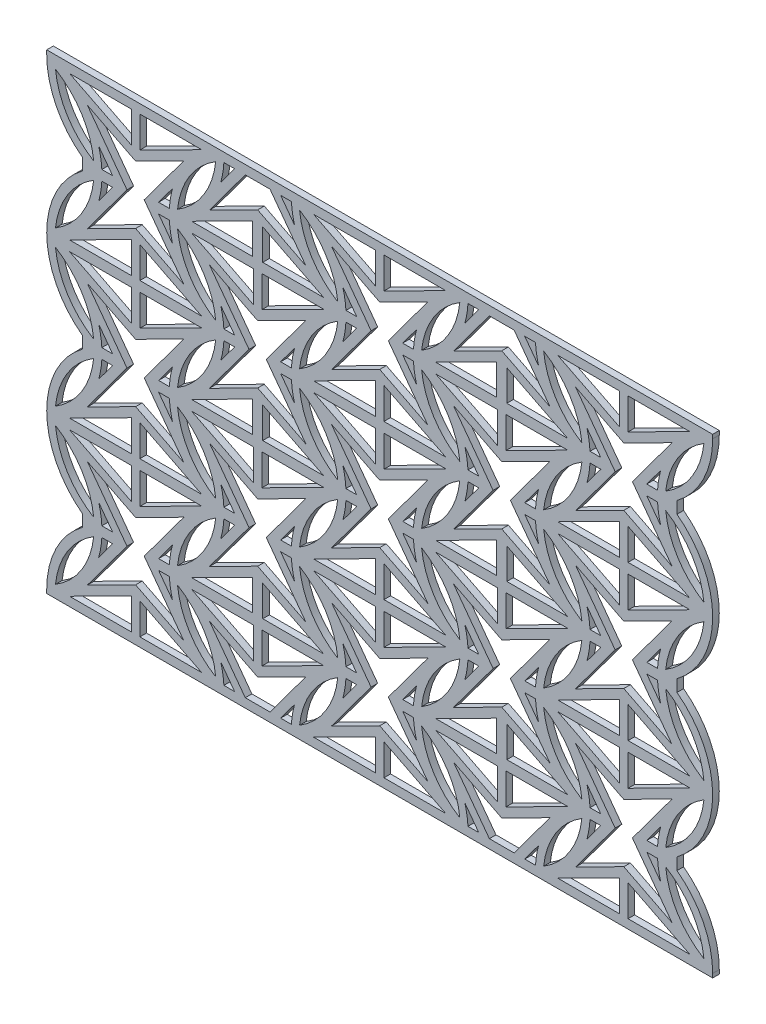
SolidWorks part; units mm, degrees
ref_plane "Front Plane" through (0, 0, 0) normal (0, 0, 1) x (1, 0, 0)
ref_plane "Top Plane" through (0, 0, 0) normal (0, 1, 0) x (1, 0, 0)
ref_plane "Right Plane" through (0, 0, 0) normal (1, 0, 0) x (0, 0, -1)
sketch "Sketch1" plane through (0, 0, 0) normal (0, 0, 1) x (1, 0, 0)
  line L1 (4.5382, 0.1047) -> (6.4871, 0.1047)
  line L3 (-15.7279, 14.9993) -> (-15.7279, 15.7158) construction
  line L6 (16.4721, 15.7158) -> (16.4721, 14.9993) construction
  line L8 (-3.7941, 0.1047) -> (-5.743, 0.1047)
  line L9 (-15.7279, -12.9529) -> (-15.7279, -13.6694)
  line L10 (-3.7941, 1.9417) -> (-6.3088, 5.3386)
  line L11 (-15.7279, -13.6694) -> (16.4721, -13.6694)
  line L13 (-9.2665, 2.1033) -> (-9.2665, -0.0569)
  line L16 (-15.7279, 14.9993) -> (16.4721, 14.9993) construction
  line L17 (12.3361, 14.0808) -> (1.1455, 14.0808)
  line L21 (4.5382, 1.9417) -> (7.053, 5.3386)
  line L23 (-0.4014, 8.4288) -> (-11.592, 14.0808)
  line L24 (4.5382, 0.1047) -> (7.053, -3.2922)
  line L25 (4.5382, 1.9417) -> (6.4871, 1.9417)
  line L27 (-3.7941, 0.1047) -> (-6.3088, -3.2922)
  line L28 (-3.7941, 1.9417) -> (-5.743, 1.9417)
  line L30 (-15.7279, 15.7158) -> (16.4721, 15.7158) construction
  line L31 (-0.4014, 14.0808) -> (-11.592, 14.0808)
  line L33 (16.4721, -13.6694) -> (16.4721, -12.9529) construction
  line L34 (-15.7279, -12.9529) -> (16.4721, -12.9529) construction
  line L36 (10.0106, 2.1033) -> (10.0106, -0.0569) construction
  line L40 (1.1455, 8.4288) -> (12.3361, 14.0808)
  line L41 (0.3721, 6.3052) -> (9.1118, 10.7193)
  line L42 (9.1118, 10.7193) -> (1.9335, 1.0232)
  line L43 (9.1118, -8.6729) -> (1.9335, 1.0232)
  line L44 (0.3721, -4.2588) -> (9.1118, -8.6729)
  line L45 (0.3721, -4.2588) -> (-8.3677, -8.6729)
  line L46 (-8.3677, -8.6729) -> (-1.1894, 1.0232)
  line L47 (-8.3677, 10.7193) -> (-1.1894, 1.0232)
  line L48 (0.3721, 6.3052) -> (-8.3677, 10.7193)
  line L49 (-1.1894, 1.0232) -> (49998.8106, 1.0232) construction
  line L50 (0.3721, 6.3052) -> (0.3721, -49993.6948) construction
  line L51 (-0.4014, 14.0808) -> (-0.4014, 8.4288)
  line L52 (1.1455, 14.0808) -> (1.1455, 8.4288)
  line L53 (21.7061, 22.405) -> (10.5155, 28.0569)
  line L54 (22.4795, 20.2814) -> (13.7398, 24.6955)
  line L55 (26.6457, 15.9179) -> (29.1604, 19.3147)
  line L56 (6.3795, 1.0232) -> (6.3795, 0.3067) construction
  line L57 (21.7061, 28.0569) -> (10.5155, 28.0569)
  line L58 (32.118, 16.0794) -> (32.118, 13.9193) construction
  line L59 (18.3134, 15.9179) -> (15.7986, 19.3147)
  line L60 (18.3134, 15.9179) -> (16.3645, 15.9179)
  line L61 (23.403, 7.5179) -> (34.4436, 1.9417)
  line L62 (26.6457, 15.9179) -> (28.5946, 15.9179)
  line L63 (6.3795, 28.9755) -> (38.5795, 28.9755) construction
  line L64 (18.3134, 14.0808) -> (16.3645, 14.0808)
  line L65 (34.4436, 1.9417) -> (23.403, 1.9417)
  line L66 (21.5561, 2.1033) -> (21.5561, 1.9417)
  line L67 (38.5795, 0.3067) -> (38.5795, 1.0232) construction
  line L68 (26.6457, 14.0808) -> (28.5946, 14.0808)
  line L69 (13.7398, 5.3032) -> (20.918, 14.9993)
  line L70 (23.253, 28.0569) -> (23.253, 22.405)
  line L71 (21.5561, 1.9417) -> (10.5155, 1.9417)
  line L72 (22.4795, 9.7173) -> (31.2192, 5.3032)
  line L73 (6.3795, 1.0232) -> (38.5795, 1.0232) construction
  line L74 (23.403, 7.5179) -> (23.403, 1.9417)
  line L75 (22.4795, 9.7173) -> (13.7398, 5.3032)
  line L76 (6.3795, 28.9755) -> (6.3795, 29.6919) construction
  line L77 (18.3134, 14.0808) -> (15.7986, 10.6839)
  line L78 (12.841, 16.0794) -> (12.841, 13.9193) construction
  line L79 (31.2192, 24.6955) -> (24.041, 14.9993)
  line L80 (21.5561, 7.5179) -> (21.5561, 2.1033)
  line L81 (22.4795, 20.2814) -> (31.2192, 24.6955)
  line L82 (6.3795, 0.3067) -> (38.5795, 0.3067) construction
  line L83 (21.7061, 28.0569) -> (21.7061, 22.405)
  line L84 (21.5561, 7.5179) -> (10.5155, 1.9417)
  line L85 (23.253, 22.405) -> (34.4436, 28.0569)
  line L86 (6.3795, 29.6919) -> (38.5795, 29.6919) construction
  line L87 (26.6457, 14.0808) -> (29.1604, 10.6839)
  line L88 (31.2192, 5.3032) -> (24.041, 14.9993)
  line L89 (38.5795, 29.6919) -> (38.5795, 28.9755) construction
  line L90 (34.4436, 28.0569) -> (23.253, 28.0569)
  line L91 (13.7398, 24.6955) -> (20.918, 14.9993)
  line L92 (43.8135, 36.3811) -> (32.6229, 42.0331)
  line L93 (44.587, 34.2575) -> (35.8472, 38.6716)
  line L94 (48.7531, 29.894) -> (51.2679, 33.2909)
  line L95 (28.487, 14.9993) -> (28.487, 14.2829) construction
  line L96 (43.8135, 42.0331) -> (32.6229, 42.0331)
  line L97 (54.2255, 30.0555) -> (54.2255, 27.8954) construction
  line L98 (40.4208, 29.894) -> (37.9061, 33.2909)
  line L99 (40.4208, 29.894) -> (38.4719, 29.894)
  line L101 (48.7531, 29.894) -> (50.702, 29.894)
  line L102 (28.487, 42.9516) -> (60.687, 42.9516) construction
  line L103 (40.4208, 28.0569) -> (38.4719, 28.0569)
  line L106 (60.687, 14.2829) -> (60.687, 14.9993) construction
  line L107 (48.7531, 28.0569) -> (50.702, 28.0569)
  line L108 (35.8472, 19.2793) -> (43.0255, 28.9755)
  line L109 (45.3604, 42.0331) -> (45.3604, 36.3811)
  line L111 (44.587, 23.6935) -> (53.3267, 19.2793)
  line L112 (28.487, 14.9993) -> (60.687, 14.9993) construction
  line L114 (44.587, 23.6935) -> (35.8472, 19.2793)
  line L115 (28.487, 42.9516) -> (28.487, 43.6681) construction
  line L116 (40.4208, 28.0569) -> (37.9061, 24.6601)
  line L117 (34.9484, 30.0555) -> (34.9484, 27.8954) construction
  line L118 (53.3267, 38.6716) -> (46.1484, 28.9755)
  line L120 (44.587, 34.2575) -> (53.3267, 38.6716)
  line L121 (28.487, 14.2829) -> (60.687, 14.2829) construction
  line L122 (43.8135, 42.0331) -> (43.8135, 36.3811)
  line L124 (45.3604, 36.3811) -> (56.551, 42.0331)
  line L125 (28.487, 43.6681) -> (60.687, 43.6681) construction
  line L126 (48.7531, 28.0569) -> (51.2679, 24.6601)
  line L127 (53.3267, 19.2793) -> (46.1484, 28.9755)
  line L128 (60.687, 43.6681) -> (60.687, 42.9516) construction
  line L129 (56.551, 42.0331) -> (45.3604, 42.0331)
  line L130 (35.8472, 38.6716) -> (43.0255, 28.9755)
  line L131 (66.6944, 37.6696) -> (75.4341, 33.2555)
  line L132 (65.921, 56.0092) -> (65.921, 50.3572)
  line L133 (82.7944, 57.6442) -> (82.7944, 56.9278) construction
  line L134 (70.8605, 43.8701) -> (73.3753, 47.267)
  line L135 (65.921, 50.3572) -> (54.7304, 56.0092)
  line L136 (66.6944, 48.2336) -> (75.4341, 52.6478)
  line L137 (50.5944, 28.9755) -> (50.5944, 28.259) construction
  line L138 (65.771, 35.4702) -> (54.7304, 29.894)
  line L139 (62.5283, 42.0331) -> (60.0135, 38.6362)
  line L140 (66.6944, 37.6696) -> (57.9547, 33.2555)
  line L141 (50.5944, 56.9278) -> (82.7944, 56.9278) construction
  line L142 (78.6585, 56.0092) -> (67.4679, 56.0092)
  line L143 (65.921, 56.0092) -> (54.7304, 56.0092)
  line L144 (57.9547, 33.2555) -> (65.1329, 42.9516)
  line L145 (50.5944, 28.259) -> (82.7944, 28.259) construction
  line L146 (75.4341, 33.2555) -> (68.2559, 42.9516)
  line L147 (62.5283, 43.8701) -> (60.0135, 47.267)
  line L148 (66.6944, 48.2336) -> (57.9547, 52.6478)
  line L149 (76.3329, 44.0317) -> (76.3329, 41.8716) construction
  line L150 (65.771, 35.4702) -> (65.771, 30.0555)
  line L151 (67.4679, 50.3572) -> (78.6585, 56.0092)
  line L152 (57.0559, 44.0317) -> (57.0559, 41.8716) construction
  line L153 (50.5944, 57.6442) -> (82.7944, 57.6442) construction
  line L154 (65.771, 29.894) -> (54.7304, 29.894)
  line L155 (78.6585, 29.894) -> (67.6179, 29.894)
  line L156 (82.7944, 28.259) -> (82.7944, 28.9755) construction
  line L157 (62.5283, 42.0331) -> (60.5794, 42.0331)
  line L158 (70.8605, 43.8701) -> (72.8095, 43.8701)
  line L159 (65.771, 30.0555) -> (65.771, 29.894)
  line L160 (67.6179, 35.4702) -> (78.6585, 29.894)
  line L161 (62.5283, 43.8701) -> (60.5794, 43.8701)
  line L162 (67.6179, 35.4702) -> (67.6179, 29.894)
  line L163 (50.5944, 28.9755) -> (82.7944, 28.9755) construction
  line L164 (70.8605, 42.0331) -> (72.8095, 42.0331)
  line L165 (70.8605, 42.0331) -> (73.3753, 38.6362)
  line L166 (75.4341, 52.6478) -> (68.2559, 42.9516)
  line L167 (57.9547, 52.6478) -> (65.1329, 42.9516)
  line L168 (50.5944, 56.9278) -> (50.5944, 57.6442) construction
  line L169 (67.4679, 56.0092) -> (67.4679, 50.3572)
  line L170 (26.6457, 43.8701) -> (29.1604, 47.267)
  line L171 (26.6457, 42.0331) -> (29.1604, 38.6362)
  line L172 (21.5561, 30.0555) -> (21.5561, 29.894)
  line L173 (23.403, 35.4702) -> (23.403, 29.894)
  line L174 (38.5795, 28.259) -> (38.5795, 28.9755) construction
  line L175 (23.403, 35.4702) -> (34.4436, 29.894)
  line L176 (23.253, 50.3572) -> (34.4436, 56.0092)
  line L177 (6.3795, 28.9755) -> (6.3795, 28.259) construction
  line L178 (34.4436, 56.0092) -> (23.253, 56.0092)
  line L179 (34.4436, 29.894) -> (23.403, 29.894)
  line L180 (22.4795, 37.6696) -> (31.2192, 33.2555)
  line L181 (6.3795, 56.9278) -> (6.3795, 57.6442) construction
  line L182 (21.7061, 50.3572) -> (10.5155, 56.0092)
  line L183 (22.4795, 37.6696) -> (13.7398, 33.2555)
  line L184 (21.5561, 35.4702) -> (21.5561, 30.0555)
  line L185 (6.3795, 56.9278) -> (38.5795, 56.9278) construction
  line L186 (21.5561, 35.4702) -> (10.5155, 29.894)
  line L187 (22.4795, 48.2336) -> (13.7398, 52.6478)
  line L188 (23.253, 56.0092) -> (23.253, 50.3572)
  line L189 (21.5561, 29.894) -> (10.5155, 29.894)
  line L190 (12.841, 44.0317) -> (12.841, 41.8716) construction
  line L191 (32.118, 44.0317) -> (32.118, 41.8716) construction
  line L192 (26.6457, 42.0331) -> (28.5946, 42.0331)
  line L193 (21.7061, 56.0092) -> (10.5155, 56.0092)
  line L194 (18.3134, 42.0331) -> (16.3645, 42.0331)
  line L195 (13.7398, 52.6478) -> (20.918, 42.9516)
  line L196 (18.3134, 43.8701) -> (16.3645, 43.8701)
  line L197 (31.2192, 33.2555) -> (24.041, 42.9516)
  line L198 (6.3795, 28.259) -> (38.5795, 28.259) construction
  line L199 (18.3134, 42.0331) -> (15.7986, 38.6362)
  line L200 (13.7398, 33.2555) -> (20.918, 42.9516)
  line L201 (22.4795, 48.2336) -> (31.2192, 52.6478)
  line L202 (38.5795, 57.6442) -> (38.5795, 56.9278) construction
  line L203 (18.3134, 43.8701) -> (15.7986, 47.267)
  line L204 (31.2192, 52.6478) -> (24.041, 42.9516)
  line L205 (6.3795, 28.9755) -> (38.5795, 28.9755) construction
  line L206 (21.7061, 56.0092) -> (21.7061, 50.3572)
  line L207 (26.6457, 43.8701) -> (28.5946, 43.8701)
  line L208 (6.3795, 57.6442) -> (38.5795, 57.6442) construction
  line L209 (4.5382, 29.894) -> (7.053, 33.2909)
  line L210 (4.5382, 28.0569) -> (7.053, 24.6601)
  line L213 (16.4721, 14.2829) -> (16.4721, 14.9993) construction
  line L215 (1.1455, 36.3811) -> (12.3361, 42.0331)
  line L216 (-15.7279, 14.9993) -> (-15.7279, 14.2829) construction
  line L217 (12.3361, 42.0331) -> (1.1455, 42.0331)
  line L219 (0.3721, 23.6935) -> (9.1118, 19.2793)
  line L220 (-15.7279, 42.9516) -> (-15.7279, 43.6681) construction
  line L221 (-0.4014, 36.3811) -> (-11.592, 42.0331)
  line L222 (0.3721, 23.6935) -> (-8.3677, 19.2793)
  line L224 (-15.7279, 42.9516) -> (16.4721, 42.9516) construction
  line L226 (0.3721, 34.2575) -> (-8.3677, 38.6716)
  line L227 (1.1455, 42.0331) -> (1.1455, 36.3811)
  line L229 (-9.2665, 30.0555) -> (-9.2665, 27.8954)
  line L230 (10.0106, 30.0555) -> (10.0106, 27.8954) construction
  line L231 (4.5382, 28.0569) -> (6.4871, 28.0569)
  line L232 (-0.4014, 42.0331) -> (-11.592, 42.0331)
  line L233 (-3.7941, 28.0569) -> (-5.743, 28.0569)
  line L234 (-8.3677, 38.6716) -> (-1.1894, 28.9755)
  line L235 (-3.7941, 29.894) -> (-5.743, 29.894)
  line L236 (9.1118, 19.2793) -> (1.9335, 28.9755)
  line L237 (-15.7279, 14.2829) -> (16.4721, 14.2829) construction
  line L238 (-3.7941, 28.0569) -> (-6.3088, 24.6601)
  line L239 (-8.3677, 19.2793) -> (-1.1894, 28.9755)
  line L240 (0.3721, 34.2575) -> (9.1118, 38.6716)
  line L241 (16.4721, 43.6681) -> (16.4721, 42.9516) construction
  line L242 (-3.7941, 29.894) -> (-6.3088, 33.2909)
  line L243 (9.1118, 38.6716) -> (1.9335, 28.9755)
  line L244 (-15.7279, 14.9993) -> (16.4721, 14.9993) construction
  line L245 (-0.4014, 42.0331) -> (-0.4014, 36.3811)
  line L246 (4.5382, 29.894) -> (6.4871, 29.894)
  line L247 (-15.7279, 43.6681) -> (16.4721, 43.6681) construction
  line L248 (48.7531, 57.8463) -> (51.2679, 61.2432)
  line L249 (48.7531, 56.0092) -> (51.2679, 52.6123)
  line L252 (60.687, 42.2352) -> (60.687, 42.9516) construction
  line L254 (45.3604, 64.3334) -> (56.551, 69.9854)
  line L255 (28.487, 42.9516) -> (28.487, 42.2352) construction
  line L256 (56.551, 69.9854) -> (45.3604, 69.9854)
  line L258 (44.587, 51.6457) -> (53.3267, 47.2316)
  line L259 (28.487, 70.9039) -> (28.487, 71.6203) construction
  line L260 (43.8135, 64.3334) -> (32.6229, 69.9854)
  line L261 (44.587, 51.6457) -> (35.8472, 47.2316)
  line L263 (28.487, 70.9039) -> (60.687, 70.9039) construction
  line L265 (44.587, 62.2098) -> (35.8472, 66.6239)
  line L266 (45.3604, 69.9854) -> (45.3604, 64.3334)
  line L268 (34.9484, 58.0078) -> (34.9484, 55.8477) construction
  line L269 (54.2255, 58.0078) -> (54.2255, 55.8477) construction
  line L270 (48.7531, 56.0092) -> (50.702, 56.0092)
  line L271 (43.8135, 69.9854) -> (32.6229, 69.9854)
  line L272 (40.4208, 56.0092) -> (38.4719, 56.0092)
  line L273 (35.8472, 66.6239) -> (43.0255, 56.9278)
  line L274 (40.4208, 57.8463) -> (38.4719, 57.8463)
  line L275 (53.3267, 47.2316) -> (46.1484, 56.9278)
  line L276 (28.487, 42.2352) -> (60.687, 42.2352) construction
  line L277 (40.4208, 56.0092) -> (37.9061, 52.6123)
  line L278 (35.8472, 47.2316) -> (43.0255, 56.9278)
  line L279 (44.587, 62.2098) -> (53.3267, 66.6239)
  line L280 (60.687, 71.6203) -> (60.687, 70.9039) construction
  line L281 (40.4208, 57.8463) -> (37.9061, 61.2432)
  line L282 (53.3267, 66.6239) -> (46.1484, 56.9278)
  line L283 (28.487, 42.9516) -> (60.687, 42.9516) construction
  line L284 (43.8135, 69.9854) -> (43.8135, 64.3334)
  line L285 (48.7531, 57.8463) -> (50.702, 57.8463)
  line L286 (28.487, 71.6203) -> (60.687, 71.6203)
  line L287 (4.5382, 57.8463) -> (7.053, 61.2432)
  line L288 (4.5382, 56.0092) -> (7.053, 52.6123)
  line L291 (16.4721, 42.2352) -> (16.4721, 42.9516) construction
  line L293 (1.1455, 64.3334) -> (12.3361, 69.9854)
  line L294 (-15.7279, 42.9516) -> (-15.7279, 42.2352) construction
  line L295 (12.3361, 69.9854) -> (1.1455, 69.9854)
  line L297 (0.3721, 51.6457) -> (9.1118, 47.2316)
  line L298 (-15.7279, 70.9039) -> (-15.7279, 71.6203)
  line L299 (-0.4014, 64.3334) -> (-11.592, 69.9854)
  line L300 (0.3721, 51.6457) -> (-8.3677, 47.2316)
  line L302 (-15.7279, 70.9039) -> (16.4721, 70.9039) construction
  line L304 (0.3721, 62.2098) -> (-8.3677, 66.6239)
  line L305 (1.1455, 69.9854) -> (1.1455, 64.3334)
  line L307 (-9.2665, 58.0078) -> (-9.2665, 55.8477)
  line L308 (10.0106, 58.0078) -> (10.0106, 55.8477) construction
  line L309 (4.5382, 56.0092) -> (6.4871, 56.0092)
  line L310 (-0.4014, 69.9854) -> (-11.592, 69.9854)
  line L311 (-3.7941, 56.0092) -> (-5.743, 56.0092)
  line L312 (-8.3677, 66.6239) -> (-1.1894, 56.9278)
  line L313 (-3.7941, 57.8463) -> (-5.743, 57.8463)
  line L314 (9.1118, 47.2316) -> (1.9335, 56.9278)
  line L315 (-15.7279, 42.2352) -> (16.4721, 42.2352) construction
  line L316 (-3.7941, 56.0092) -> (-6.3088, 52.6123)
  line L317 (-8.3677, 47.2316) -> (-1.1894, 56.9278)
  line L318 (0.3721, 62.2098) -> (9.1118, 66.6239)
  line L319 (16.4721, 71.6203) -> (16.4721, 70.9039) construction
  line L320 (-3.7941, 57.8463) -> (-6.3088, 61.2432)
  line L321 (9.1118, 66.6239) -> (1.9335, 56.9278)
  line L322 (-15.7279, 42.9516) -> (16.4721, 42.9516) construction
  line L323 (-0.4014, 69.9854) -> (-0.4014, 64.3334)
  line L324 (4.5382, 57.8463) -> (6.4871, 57.8463)
  line L325 (-15.7279, 71.6203) -> (16.4721, 71.6203)
  line L326 (26.6457, 71.8224) -> (29.1604, 75.2193) construction
  line L327 (26.6457, 69.9854) -> (29.1604, 66.5885)
  line L328 (21.5561, 58.0078) -> (21.5561, 57.8463)
  line L329 (23.403, 63.4225) -> (23.403, 57.8463)
  line L330 (38.5795, 56.2113) -> (38.5795, 56.9278) construction
  line L331 (23.403, 63.4225) -> (34.4436, 57.8463)
  line L332 (23.253, 78.3095) -> (34.4436, 83.9615) construction
  line L333 (6.3795, 56.9278) -> (6.3795, 56.2113) construction
  line L334 (34.4436, 83.9615) -> (23.253, 83.9615) construction
  line L335 (34.4436, 57.8463) -> (23.403, 57.8463)
  line L336 (22.4795, 65.6219) -> (31.2192, 61.2078)
  line L337 (6.3795, 84.88) -> (6.3795, 85.5965) construction
  line L338 (21.7061, 78.3095) -> (10.5155, 83.9615) construction
  line L339 (22.4795, 65.6219) -> (13.7398, 61.2078)
  line L340 (21.5561, 63.4225) -> (21.5561, 58.0078)
  line L341 (6.3795, 84.88) -> (38.5795, 84.88) construction
  line L342 (21.5561, 63.4225) -> (10.5155, 57.8463)
  line L344 (23.253, 83.9615) -> (23.253, 78.3095) construction
  line L345 (21.5561, 57.8463) -> (10.5155, 57.8463)
  line L346 (12.841, 71.9839) -> (12.841, 69.8665) construction
  line L347 (32.118, 71.9839) -> (32.118, 69.7811) construction
  line L348 (26.6457, 69.9854) -> (28.5946, 69.9854)
  line L349 (21.7061, 83.9615) -> (10.5155, 83.9615) construction
  line L350 (18.3134, 69.9854) -> (16.3645, 69.9854)
  line L352 (18.3134, 71.8224) -> (16.3645, 71.8224) construction
  line L353 (31.2192, 61.2078) -> (24.721, 69.9854)
  line L354 (6.3795, 56.2113) -> (38.5795, 56.2113) construction
  line L355 (18.3134, 69.9854) -> (15.7986, 66.5885)
  line L356 (13.7398, 61.2078) -> (20.238, 69.9854)
  line L358 (38.5795, 85.5965) -> (38.5795, 84.88) construction
  line L359 (18.3134, 71.8224) -> (15.7986, 75.2193) construction
  line L361 (6.3795, 56.9278) -> (38.5795, 56.9278) construction
  line L362 (21.7061, 83.9615) -> (21.7061, 78.3095) construction
  line L363 (26.6457, 71.8224) -> (28.5946, 71.8224) construction
  line L364 (6.3795, 85.5965) -> (38.5795, 85.5965) construction
  line L365 (53.3267, 10.7193) -> (46.1484, 1.0232)
  line L366 (44.587, 6.3052) -> (35.8472, 10.7193)
  line L367 (28.487, -13.6694) -> (60.687, -13.6694)
  line L368 (40.4208, 0.1047) -> (37.9061, -3.2922)
  line L369 (54.2255, 2.1033) -> (54.2255, -0.0569) construction
  line L370 (43.8135, 8.4288) -> (32.6229, 14.0808)
  line L371 (28.487, -12.9529) -> (28.487, -13.6694) construction
  line L373 (28.487, 15.7158) -> (60.687, 15.7158) construction
  line L374 (48.7531, 0.1047) -> (51.2679, -3.2922)
  line L375 (28.487, 14.9993) -> (28.487, 15.7158) construction
  line L376 (48.7531, 0.1047) -> (50.702, 0.1047)
  line L377 (45.3604, 8.4288) -> (56.551, 14.0808)
  line L378 (35.8472, 10.7193) -> (43.0255, 1.0232)
  line L379 (40.4208, 1.9417) -> (37.9061, 5.3386)
  line L381 (44.587, -4.2588) -> (35.8472, -8.6729)
  line L382 (40.4208, 0.1047) -> (38.4719, 0.1047)
  line L383 (48.7531, 1.9417) -> (50.702, 1.9417)
  line L384 (34.9484, 2.1033) -> (34.9484, -0.0569) construction
  line L385 (56.551, 14.0808) -> (45.3604, 14.0808)
  line L386 (48.7531, 1.9417) -> (51.2679, 5.3386)
  line L387 (43.8135, 14.0808) -> (32.6229, 14.0808)
  line L388 (28.487, -12.9529) -> (60.687, -12.9529) construction
  line L390 (35.8472, -8.6729) -> (43.0255, 1.0232)
  line L391 (28.487, 14.9993) -> (60.687, 14.9993) construction
  line L393 (53.3267, -8.6729) -> (46.1484, 1.0232)
  line L394 (60.687, -13.6694) -> (60.687, -12.9529) construction
  line L395 (40.4208, 1.9417) -> (38.4719, 1.9417)
  line L396 (43.8135, 14.0808) -> (43.8135, 8.4288)
  line L398 (44.587, 6.3052) -> (53.3267, 10.7193)
  line L400 (44.587, -4.2588) -> (53.3267, -8.6729)
  line L402 (45.3604, 14.0808) -> (45.3604, 8.4288)
  line L403 (60.687, 15.7158) -> (60.687, 14.9993) construction
  line L404 (75.4341, 24.6955) -> (68.2559, 14.9993)
  line L405 (66.6944, 20.2814) -> (57.9547, 24.6955)
  line L406 (50.5944, 0.3067) -> (82.7944, 0.3067) construction
  line L407 (62.5283, 14.0808) -> (60.0135, 10.6839)
  line L408 (76.3329, 16.0794) -> (76.3329, 13.9193) construction
  line L409 (65.921, 22.405) -> (54.7304, 28.0569)
  line L410 (50.5944, 1.0232) -> (50.5944, 0.3067) construction
  line L411 (67.6179, 7.5179) -> (78.6585, 1.9417)
  line L412 (50.5944, 29.6919) -> (82.7944, 29.6919) construction
  line L413 (70.8605, 14.0808) -> (73.3753, 10.6839)
  line L414 (50.5944, 28.9755) -> (50.5944, 29.6919) construction
  line L415 (70.8605, 14.0808) -> (72.8095, 14.0808)
  line L416 (67.4679, 22.405) -> (78.6585, 28.0569)
  line L417 (57.9547, 24.6955) -> (65.1329, 14.9993)
  line L418 (62.5283, 15.9179) -> (60.0135, 19.3147)
  line L419 (78.6585, 1.9417) -> (67.6179, 1.9417)
  line L420 (66.6944, 9.7173) -> (57.9547, 5.3032)
  line L421 (62.5283, 14.0808) -> (60.5794, 14.0808)
  line L422 (70.8605, 15.9179) -> (72.8095, 15.9179)
  line L423 (57.0559, 16.0794) -> (57.0559, 13.9193) construction
  line L424 (78.6585, 28.0569) -> (67.4679, 28.0569)
  line L425 (70.8605, 15.9179) -> (73.3753, 19.3147)
  line L426 (65.921, 28.0569) -> (54.7304, 28.0569)
  line L427 (50.5944, 1.0232) -> (82.7944, 1.0232) construction
  line L428 (67.6179, 7.5179) -> (67.6179, 1.9417)
  line L429 (57.9547, 5.3032) -> (65.1329, 14.9993)
  line L430 (50.5944, 28.9755) -> (82.7944, 28.9755) construction
  line L431 (65.771, 1.9417) -> (54.7304, 1.9417)
  line L432 (75.4341, 5.3032) -> (68.2559, 14.9993)
  line L433 (82.7944, 0.3067) -> (82.7944, 1.0232) construction
  line L434 (62.5283, 15.9179) -> (60.5794, 15.9179)
  line L435 (65.921, 28.0569) -> (65.921, 22.405)
  line L436 (65.771, 7.5179) -> (65.771, 2.1033)
  line L437 (66.6944, 20.2814) -> (75.4341, 24.6955)
  line L438 (65.771, 7.5179) -> (54.7304, 1.9417)
  line L439 (66.6944, 9.7173) -> (75.4341, 5.3032)
  line L440 (65.771, 2.1033) -> (65.771, 1.9417)
  line L441 (67.4679, 28.0569) -> (67.4679, 22.405)
  line L442 (82.7944, 29.6919) -> (82.7944, 28.9755) construction
  line L443 (65.921, 83.9615) -> (54.7304, 83.9615) construction
  line L444 (67.4679, 78.3095) -> (78.6585, 83.9615) construction
  line L446 (78.6585, 83.9615) -> (67.4679, 83.9615) construction
  line L448 (82.7944, 85.5965) -> (82.7944, 84.88) construction
  line L449 (66.6944, 65.6219) -> (57.9547, 61.2078)
  line L450 (50.5944, 84.88) -> (50.5944, 85.5965) construction
  line L451 (57.0559, 71.9839) -> (57.0559, 69.8238) construction
  line L452 (70.8605, 69.9854) -> (73.3753, 66.5885)
  line L454 (82.7944, 56.2113) -> (82.7944, 56.9278) construction
  line L455 (62.5283, 71.8224) -> (60.0135, 75.2193) construction
  line L456 (62.5283, 69.9854) -> (60.0135, 66.5885)
  line L457 (65.921, 83.9615) -> (65.921, 78.3095) construction
  line L458 (76.3329, 71.9839) -> (76.3329, 69.8238) construction
  line L459 (70.8605, 69.9854) -> (72.8095, 69.9854)
  line L460 (70.8605, 71.8224) -> (72.8095, 71.8224) construction
  line L461 (67.6179, 63.4225) -> (78.6585, 57.8463)
  line L462 (65.921, 78.3095) -> (54.7304, 83.9615) construction
  line L463 (65.771, 63.4225) -> (65.771, 58.0078)
  line L464 (67.6179, 63.4225) -> (67.6179, 57.8463)
  line L465 (70.8605, 71.8224) -> (73.3753, 75.2193) construction
  line L467 (67.4679, 83.9615) -> (67.4679, 78.3095) construction
  line L468 (50.5944, 56.9278) -> (82.7944, 56.9278) construction
  line L469 (78.6585, 57.8463) -> (67.6179, 57.8463)
  line L470 (75.4341, 61.2078) -> (68.9359, 69.9854)
  line L471 (50.5944, 56.2113) -> (82.7944, 56.2113) construction
  line L472 (65.771, 57.8463) -> (54.7304, 57.8463)
  line L473 (66.6944, 65.6219) -> (75.4341, 61.2078)
  line L474 (50.5944, 85.5965) -> (82.7944, 85.5965) construction
  line L475 (62.5283, 69.9854) -> (60.5794, 69.9854)
  line L476 (50.5944, 56.9278) -> (50.5944, 56.2113) construction
  line L477 (65.771, 63.4225) -> (54.7304, 57.8463)
  line L478 (57.9547, 61.2078) -> (64.4529, 69.9854)
  line L479 (50.5944, 84.88) -> (82.7944, 84.88) construction
  line L480 (65.771, 58.0078) -> (65.771, 57.8463)
  line L481 (62.5283, 71.8224) -> (60.5794, 71.8224) construction
  line L483 (89.5753, 42.0331) -> (89.5753, 36.3811)
  line L484 (72.7019, 43.6681) -> (104.9019, 43.6681) construction
  line L485 (84.6357, 29.894) -> (82.121, 33.2909)
  line L486 (92.968, 29.894) -> (94.9169, 29.894)
  line L487 (88.8019, 34.2575) -> (80.0621, 38.6716)
  line L488 (72.7019, 14.9993) -> (72.7019, 14.2829) construction
  line L489 (92.968, 29.894) -> (95.4828, 33.2909)
  line L490 (80.0621, 38.6716) -> (87.2404, 28.9755)
  line L491 (88.0284, 42.0331) -> (88.0284, 36.3811)
  line L493 (104.9019, 43.6681) -> (104.9019, 42.9516) construction
  line L494 (104.9019, 14.2829) -> (104.9019, 14.9993) construction
  line L496 (97.5416, 38.6716) -> (90.3633, 28.9755)
  line L499 (84.6357, 28.0569) -> (82.6868, 28.0569)
  line L500 (88.8019, 23.6935) -> (80.0621, 19.2793)
  line L501 (72.7019, 42.9516) -> (72.7019, 43.6681) construction
  line L503 (88.8019, 34.2575) -> (97.5416, 38.6716)
  line L504 (92.968, 28.0569) -> (94.9169, 28.0569)
  line L505 (92.968, 28.0569) -> (95.4828, 24.6601)
  line L506 (79.1633, 30.0555) -> (79.1633, 27.8954) construction
  line L507 (72.7019, 14.9993) -> (104.9019, 14.9993) construction
  line L508 (88.0284, 36.3811) -> (76.8378, 42.0331)
  line L509 (88.0284, 42.0331) -> (76.8378, 42.0331)
  line L510 (98.4404, 30.0555) -> (98.4404, 27.8954)
  line L511 (84.6357, 28.0569) -> (82.121, 24.6601)
  line L512 (84.6357, 29.894) -> (82.6868, 29.894)
  line L513 (89.5753, 36.3811) -> (100.7659, 42.0331)
  line L514 (72.7019, 42.9516) -> (104.9019, 42.9516) construction
  line L515 (88.8019, 23.6935) -> (97.5416, 19.2793)
  line L516 (100.7659, 42.0331) -> (89.5753, 42.0331)
  line L517 (97.5416, 19.2793) -> (90.3633, 28.9755)
  line L519 (80.0621, 19.2793) -> (87.2404, 28.9755)
  line L520 (72.7019, 14.2829) -> (104.9019, 14.2829) construction
  line L522 (89.5753, 69.9854) -> (89.5753, 64.3334)
  line L523 (72.7019, 71.6203) -> (104.9019, 71.6203)
  line L524 (84.6357, 57.8463) -> (82.121, 61.2432)
  line L525 (92.968, 57.8463) -> (94.9169, 57.8463)
  line L526 (88.8019, 62.2098) -> (80.0621, 66.6239)
  line L527 (72.7019, 42.9516) -> (72.7019, 42.2352) construction
  line L528 (92.968, 57.8463) -> (95.4828, 61.2432)
  line L529 (80.0621, 66.6239) -> (87.2404, 56.9278)
  line L530 (88.0284, 69.9854) -> (88.0284, 64.3334)
  line L532 (104.9019, 71.6203) -> (104.9019, 70.9039)
  line L533 (104.9019, 42.2352) -> (104.9019, 42.9516) construction
  line L535 (97.5416, 66.6239) -> (90.3633, 56.9278)
  line L538 (84.6357, 56.0092) -> (82.6868, 56.0092)
  line L539 (88.8019, 51.6457) -> (80.0621, 47.2316)
  line L540 (72.7019, 70.9039) -> (72.7019, 71.6203) construction
  line L542 (88.8019, 62.2098) -> (97.5416, 66.6239)
  line L543 (92.968, 56.0092) -> (94.9169, 56.0092)
  line L544 (92.968, 56.0092) -> (95.4828, 52.6123)
  line L545 (79.1633, 58.0078) -> (79.1633, 55.8477) construction
  line L546 (72.7019, 42.9516) -> (104.9019, 42.9516) construction
  line L547 (88.0284, 64.3334) -> (76.8378, 69.9854)
  line L548 (88.0284, 69.9854) -> (76.8378, 69.9854)
  line L549 (98.4404, 58.0078) -> (98.4404, 55.8477)
  line L550 (84.6357, 56.0092) -> (82.121, 52.6123)
  line L551 (84.6357, 57.8463) -> (82.6868, 57.8463)
  line L552 (89.5753, 64.3334) -> (100.7659, 69.9854)
  line L553 (72.7019, 70.9039) -> (104.9019, 70.9039) construction
  line L554 (88.8019, 51.6457) -> (97.5416, 47.2316)
  line L555 (100.7659, 69.9854) -> (89.5753, 69.9854)
  line L556 (97.5416, 47.2316) -> (90.3633, 56.9278)
  line L558 (80.0621, 47.2316) -> (87.2404, 56.9278)
  line L559 (72.7019, 42.2352) -> (104.9019, 42.2352) construction
  line L560 (84.6357, 0.1047) -> (82.6868, 0.1047)
  line L561 (72.7019, -12.9529) -> (104.9019, -12.9529) construction
  line L562 (89.5753, 8.4288) -> (100.7659, 14.0808)
  line L565 (97.5416, -8.6729) -> (90.3633, 1.0232)
  line L566 (89.5753, 14.0808) -> (89.5753, 8.4288)
  line L567 (92.968, 0.1047) -> (95.4828, -3.2922)
  line L568 (98.4404, 2.1033) -> (98.4404, -0.0569)
  line L570 (72.7019, -12.9529) -> (72.7019, -13.6694) construction
  line L571 (80.0621, -8.6729) -> (87.2404, 1.0232)
  line L573 (88.8019, -4.2588) -> (80.0621, -8.6729)
  line L575 (88.8019, 6.3052) -> (97.5416, 10.7193)
  line L576 (72.7019, -13.6694) -> (104.9019, -13.6694)
  line L577 (84.6357, 1.9417) -> (82.121, 5.3386)
  line L578 (92.968, 1.9417) -> (94.9169, 1.9417)
  line L579 (80.0621, 10.7193) -> (87.2404, 1.0232)
  line L580 (79.1633, 2.1033) -> (79.1633, -0.0569) construction
  line L581 (84.6357, 1.9417) -> (82.6868, 1.9417)
  line L582 (97.5416, 10.7193) -> (90.3633, 1.0232)
  line L583 (92.968, 1.9417) -> (95.4828, 5.3386)
  line L584 (72.7019, 15.7158) -> (104.9019, 15.7158) construction
  line L585 (88.0284, 14.0808) -> (76.8378, 14.0808)
  line L586 (88.0284, 8.4288) -> (76.8378, 14.0808)
  line L587 (84.6357, 0.1047) -> (82.121, -3.2922)
  line L588 (92.968, 0.1047) -> (94.9169, 0.1047)
  line L589 (88.8019, -4.2588) -> (97.5416, -8.6729)
  line L590 (100.7659, 14.0808) -> (89.5753, 14.0808)
  line L592 (88.8019, 6.3052) -> (80.0621, 10.7193)
  line L593 (88.0284, 14.0808) -> (88.0284, 8.4288)
  line L595 (72.7019, 14.9993) -> (104.9019, 14.9993) construction
  line L596 (62.5283, -13.8715) -> (60.5794, -13.8715) construction
  line L597 (50.5944, -26.9291) -> (82.7944, -26.9291) construction
  line L598 (67.4679, -5.5473) -> (78.6585, 0.1047)
  line L599 (65.771, -20.4343) -> (65.771, -25.849) construction
  line L600 (65.771, -20.4343) -> (54.7304, -26.0106) construction
  line L602 (67.4679, 0.1047) -> (67.4679, -5.5473)
  line L603 (70.8605, -13.8715) -> (73.3753, -17.2684) construction
  line L604 (76.3329, -11.8729) -> (76.3329, -14.033) construction
  line L605 (65.771, -25.849) -> (65.771, -26.0106) construction
  line L606 (50.5944, -26.9291) -> (50.5944, -27.6455) construction
  line L608 (65.771, -26.0106) -> (54.7304, -26.0106) construction
  line L610 (78.6585, -26.0106) -> (67.6179, -26.0106) construction
  line L611 (66.6944, -7.6709) -> (75.4341, -3.2568)
  line L612 (50.5944, -27.6455) -> (82.7944, -27.6455) construction
  line L613 (62.5283, -12.0344) -> (60.0135, -8.6375)
  line L614 (70.8605, -12.0344) -> (72.8095, -12.0344)
  line L615 (57.9547, -3.2568) -> (64.4529, -12.0344)
  line L616 (57.0559, -11.8729) -> (57.0559, -14.033) construction
  line L617 (62.5283, -12.0344) -> (60.5794, -12.0344)
  line L618 (75.4341, -3.2568) -> (68.9359, -12.0344)
  line L619 (70.8605, -12.0344) -> (73.3753, -8.6375)
  line L620 (50.5944, 1.7396) -> (82.7944, 1.7396) construction
  line L621 (65.921, 0.1047) -> (54.7304, 0.1047)
  line L622 (65.921, -5.5473) -> (54.7304, 0.1047)
  line L623 (62.5283, -13.8715) -> (60.0135, -17.2684) construction
  line L624 (70.8605, -13.8715) -> (72.8095, -13.8715) construction
  line L626 (78.6585, 0.1047) -> (67.4679, 0.1047)
  line L627 (67.6179, -20.4343) -> (67.6179, -26.0106) construction
  line L628 (66.6944, -7.6709) -> (57.9547, -3.2568)
  line L629 (65.921, 0.1047) -> (65.921, -5.5473)
  line L630 (67.6179, -20.4343) -> (78.6585, -26.0106) construction
  line L631 (50.5944, 1.0232) -> (82.7944, 1.0232) construction
  line L632 (18.3134, -13.8715) -> (16.3645, -13.8715) construction
  line L633 (6.3795, -26.9291) -> (38.5795, -26.9291) construction
  line L634 (23.253, -5.5473) -> (34.4436, 0.1047)
  line L635 (21.5561, -20.4343) -> (21.5561, -25.849) construction
  line L636 (21.5561, -20.4343) -> (10.5155, -26.0106) construction
  line L638 (23.253, 0.1047) -> (23.253, -5.5473)
  line L639 (26.6457, -13.8715) -> (29.1604, -17.2684) construction
  line L640 (32.118, -11.8729) -> (32.118, -14.033) construction
  line L641 (21.5561, -25.849) -> (21.5561, -26.0106) construction
  line L642 (6.3795, -26.9291) -> (6.3795, -27.6455) construction
  line L644 (21.5561, -26.0106) -> (10.5155, -26.0106) construction
  line L646 (34.4436, -26.0106) -> (23.403, -26.0106) construction
  line L647 (22.4795, -7.6709) -> (31.2192, -3.2568)
  line L648 (6.3795, -27.6455) -> (38.5795, -27.6455) construction
  line L649 (18.3134, -12.0344) -> (15.7986, -8.6375)
  line L650 (26.6457, -12.0344) -> (28.5946, -12.0344)
  line L651 (13.7398, -3.2568) -> (20.238, -12.0344)
  line L652 (12.841, -11.8729) -> (12.841, -14.033) construction
  line L653 (18.3134, -12.0344) -> (16.3645, -12.0344)
  line L654 (31.2192, -3.2568) -> (24.721, -12.0344)
  line L655 (26.6457, -12.0344) -> (29.1604, -8.6375)
  line L656 (6.3795, 1.7396) -> (38.5795, 1.7396) construction
  line L657 (21.7061, 0.1047) -> (10.5155, 0.1047)
  line L658 (21.7061, -5.5473) -> (10.5155, 0.1047)
  line L659 (18.3134, -13.8715) -> (15.7986, -17.2684) construction
  line L660 (26.6457, -13.8715) -> (28.5946, -13.8715) construction
  line L662 (34.4436, 0.1047) -> (23.253, 0.1047)
  line L663 (23.403, -20.4343) -> (23.403, -26.0106) construction
  line L664 (22.4795, -7.6709) -> (13.7398, -3.2568)
  line L665 (21.7061, 0.1047) -> (21.7061, -5.5473)
  line L666 (23.403, -20.4343) -> (34.4436, -26.0106) construction
  line L667 (6.3795, 1.0232) -> (38.5795, 1.0232) construction
  line L668 (16.4721, -13.6694) -> (28.487, -13.6694)
  line L669 (60.687, -13.6694) -> (72.7019, -13.6694)
  line L670 (16.4721, 71.6203) -> (28.487, 71.6203)
  line L671 (60.687, 71.6203) -> (72.7019, 71.6203)
  line L672 (64.4529, 69.9854) -> (68.9359, 69.9854)
  line L673 (20.238, 69.9854) -> (24.721, 69.9854)
  line L674 (20.238, -12.0344) -> (24.721, -12.0344)
  line L675 (64.4529, -12.0344) -> (68.9359, -12.0344)
  line L676 (104.9019, -12.9529) -> (104.9019, -13.6694)
  line L677 (89.5753, -12.0344) -> (89.5753, -6.3824)
  line L678 (100.7659, -12.0344) -> (89.5753, -12.0344)
  line L679 (89.5753, -6.3824) -> (100.7659, -12.0344)
  line L680 (88.0284, -12.0344) -> (88.0284, -6.3824)
  line L681 (88.0284, -6.3824) -> (76.8378, -12.0344)
  line L682 (88.0284, -12.0344) -> (76.8378, -12.0344)
  line L683 (45.3604, -12.0344) -> (45.3604, -6.3824)
  line L684 (56.551, -12.0344) -> (45.3604, -12.0344)
  line L685 (45.3604, -6.3824) -> (56.551, -12.0344)
  line L686 (43.8135, -12.0344) -> (43.8135, -6.3824)
  line L687 (43.8135, -12.0344) -> (32.6229, -12.0344)
  line L688 (43.8135, -6.3824) -> (32.6229, -12.0344)
  line L689 (1.1455, -6.3824) -> (12.3361, -12.0344)
  line L690 (1.1455, -12.0344) -> (1.1455, -6.3824)
  line L691 (12.3361, -12.0344) -> (1.1455, -12.0344)
  line L692 (-0.4014, -12.0344) -> (-0.4014, -6.3824)
  line L693 (-0.4014, -6.3824) -> (-11.592, -12.0344)
  line L694 (-0.4014, -12.0344) -> (-11.592, -12.0344)
  line L695 (-1.1894, 28.9755) -> (1.9335, 28.9755) construction
  line L696 (-1.1894, 56.9278) -> (1.9335, 56.9278) construction
  line L697 (100.7659, 15.9179) -> (89.5753, 15.9179)
  line L698 (89.5753, 21.5698) -> (100.7659, 15.9179)
  line L699 (89.5753, 15.9179) -> (89.5753, 21.5698)
  line L700 (88.0284, 15.9179) -> (76.8378, 15.9179)
  line L701 (88.0284, 21.5698) -> (76.8378, 15.9179)
  line L702 (88.0284, 15.9179) -> (88.0284, 21.5698)
  line L703 (56.551, 15.9179) -> (45.3604, 15.9179)
  line L704 (45.3604, 21.5698) -> (56.551, 15.9179)
  line L705 (45.3604, 15.9179) -> (45.3604, 21.5698)
  line L706 (43.8135, 15.9179) -> (43.8135, 21.5698)
  line L707 (43.8135, 15.9179) -> (32.6229, 15.9179)
  line L708 (43.8135, 21.5698) -> (32.6229, 15.9179)
  line L709 (1.1455, 15.9179) -> (1.1455, 21.5698)
  line L710 (12.3361, 15.9179) -> (1.1455, 15.9179)
  line L711 (1.1455, 21.5698) -> (12.3361, 15.9179)
  line L712 (-0.4014, 15.9179) -> (-0.4014, 21.5698)
  line L713 (-0.4014, 15.9179) -> (-11.592, 15.9179)
  line L714 (-0.4014, 21.5698) -> (-11.592, 15.9179)
  line L715 (100.7659, 43.8701) -> (89.5753, 43.8701)
  line L716 (89.5753, 49.5221) -> (100.7659, 43.8701)
  line L717 (89.5753, 43.8701) -> (89.5753, 49.5221)
  line L718 (88.0284, 43.8701) -> (76.8378, 43.8701)
  line L719 (88.0284, 49.5221) -> (76.8378, 43.8701)
  line L720 (88.0284, 43.8701) -> (88.0284, 49.5221)
  line L721 (45.3604, 43.8701) -> (45.3604, 49.5221)
  line L722 (56.551, 43.8701) -> (45.3604, 43.8701)
  line L723 (45.3604, 49.5221) -> (56.551, 43.8701)
  line L724 (43.8135, 43.8701) -> (43.8135, 49.5221)
  line L725 (43.8135, 43.8701) -> (32.6229, 43.8701)
  line L726 (43.8135, 49.5221) -> (32.6229, 43.8701)
  line L727 (1.1455, 43.8701) -> (1.1455, 49.5221)
  line L728 (12.3361, 43.8701) -> (1.1455, 43.8701)
  line L729 (1.1455, 49.5221) -> (12.3361, 43.8701)
  line L730 (-0.4014, 43.8701) -> (-0.4014, 49.5221)
  line L731 (-0.4014, 43.8701) -> (-11.592, 43.8701)
  line L732 (-0.4014, 49.5221) -> (-11.592, 43.8701)
  arc A0 (-5.743, 0.1047) -> (-6.3088, -3.2922) centre (-21.7354, 1.0232) cw
  arc A2 (-14.1405, -11.436) -> (-7.2229, -0.4937) centre (-21.7354, 1.0232) ccw
  arc A3 (7.967, 2.5401) -> (14.8846, 13.4824) centre (0.3721, 14.9993) ccw
  arc A4 (16.4721, 14.9993) -> (10.0106, 2.1033) centre (0.3721, 14.9993) cw construction
  arc A5 (-15.7279, 14.9993) -> (-9.2665, 2.1033) centre (0.3721, 14.9993) ccw
  arc A6 (-14.1405, 13.4824) -> (-7.2229, 2.5401) centre (-21.7354, 1.0232) cw
  arc A7 (-7.2229, -0.4937) -> (-14.1405, -11.436) centre (0.3721, -12.9529) ccw
  arc A9 (-5.743, 1.9417) -> (-6.3088, 5.3386) centre (-21.7354, 1.0232) ccw
  arc A10 (10.0106, -0.0569) -> (16.4721, -12.9529) centre (0.3721, -12.9529) cw construction
  arc A11 (-7.2229, 2.5401) -> (-14.1405, 13.4824) centre (0.3721, 14.9993) cw
  arc A12 (6.4871, 0.1047) -> (7.053, -3.2922) centre (22.4795, 1.0232) ccw
  arc A13 (6.4871, 1.9417) -> (7.053, 5.3386) centre (22.4795, 1.0232) cw
  arc A14 (-9.2665, -0.0569) -> (-15.7279, -12.9529) centre (0.3721, -12.9529) ccw
  arc A15 (14.8846, 13.4824) -> (7.967, 2.5401) centre (22.4795, 1.0232) ccw
  arc A17 (16.3645, 14.0808) -> (15.7986, 10.6839) centre (0.3721, 14.9993) cw
  arc A18 (16.3645, 15.9179) -> (15.7986, 19.3147) centre (0.3721, 14.9993) ccw
  arc A19 (36.992, 2.5401) -> (30.0744, 13.4824) centre (44.587, 14.9993) cw
  arc A20 (38.5795, 28.9755) -> (32.118, 16.0794) centre (22.4795, 28.9755) cw construction
  arc A21 (12.841, 13.9193) -> (6.3795, 1.0232) centre (22.4795, 1.0232) ccw construction
  arc A22 (30.0744, 13.4824) -> (36.992, 2.5401) centre (22.4795, 1.0232) cw
  arc A23 (36.992, 27.4585) -> (30.0744, 16.5163) centre (44.587, 14.9993) ccw
  arc A24 (32.118, 13.9193) -> (38.5795, 1.0232) centre (22.4795, 1.0232) cw construction
  arc A28 (28.5946, 14.0808) -> (29.1604, 10.6839) centre (44.587, 14.9993) ccw
  arc A29 (28.5946, 15.9179) -> (29.1604, 19.3147) centre (44.587, 14.9993) cw
  arc A30 (6.3795, 28.9755) -> (12.841, 16.0794) centre (22.4795, 28.9755) ccw construction
  arc A31 (30.0744, 16.5163) -> (36.992, 27.4585) centre (22.4795, 28.9755) ccw
  arc A33 (38.4719, 28.0569) -> (37.9061, 24.6601) centre (22.4795, 28.9755) cw
  arc A34 (38.4719, 29.894) -> (37.9061, 33.2909) centre (22.4795, 28.9755) ccw
  arc A35 (59.0995, 16.5163) -> (52.1819, 27.4585) centre (66.6944, 28.9755) cw
  arc A36 (60.687, 42.9516) -> (54.2255, 30.0555) centre (44.587, 42.9516) cw construction
  arc A37 (34.9484, 27.8954) -> (28.487, 14.9993) centre (44.587, 14.9993) ccw construction
  arc A38 (52.1819, 27.4585) -> (59.0995, 16.5163) centre (44.587, 14.9993) cw
  arc A39 (59.0995, 41.4347) -> (52.1819, 30.4924) centre (66.6944, 28.9755) ccw
  arc A40 (54.2255, 27.8954) -> (60.687, 14.9993) centre (44.587, 14.9993) cw construction
  arc A44 (50.702, 28.0569) -> (51.2679, 24.6601) centre (66.6944, 28.9755) ccw
  arc A45 (50.702, 29.894) -> (51.2679, 33.2909) centre (66.6944, 28.9755) cw
  arc A46 (28.487, 42.9516) -> (34.9484, 30.0555) centre (44.587, 42.9516) ccw construction
  arc A47 (52.1819, 30.4924) -> (59.0995, 41.4347) centre (44.587, 42.9516) ccw
  arc A48 (81.2069, 30.4924) -> (74.2893, 41.4347) centre (88.8019, 42.9516) cw
  arc A51 (76.3329, 41.8716) -> (82.7944, 28.9755) centre (66.6944, 28.9755) cw construction
  arc A52 (57.0559, 41.8716) -> (50.5944, 28.9755) centre (66.6944, 28.9755) ccw construction
  arc A53 (60.5794, 43.8701) -> (60.0135, 47.267) centre (44.587, 42.9516) ccw
  arc A54 (82.7944, 56.9278) -> (76.3329, 44.0317) centre (66.6944, 56.9278) cw construction
  arc A56 (74.2893, 41.4347) -> (81.2069, 30.4924) centre (66.6944, 28.9755) cw
  arc A57 (60.5794, 42.0331) -> (60.0135, 38.6362) centre (44.587, 42.9516) cw
  arc A58 (74.2893, 44.4686) -> (81.2069, 55.4108) centre (66.6944, 56.9278) ccw
  arc A59 (81.2069, 55.4108) -> (74.2893, 44.4686) centre (88.8019, 42.9516) ccw
  arc A61 (72.8095, 43.8701) -> (73.3753, 47.267) centre (88.8019, 42.9516) cw
  arc A62 (72.8095, 42.0331) -> (73.3753, 38.6362) centre (88.8019, 42.9516) ccw
  arc A63 (50.5944, 56.9278) -> (57.0559, 44.0317) centre (66.6944, 56.9278) ccw construction
  arc A65 (6.3795, 56.9278) -> (12.841, 44.0317) centre (22.4795, 56.9278) ccw construction
  arc A67 (30.0744, 41.4347) -> (36.992, 30.4924) centre (22.4795, 28.9755) cw
  arc A69 (28.5946, 43.8701) -> (29.1604, 47.267) centre (44.587, 42.9516) cw
  arc A71 (38.5795, 56.9278) -> (32.118, 44.0317) centre (22.4795, 56.9278) cw construction
  arc A72 (30.0744, 44.4686) -> (36.992, 55.4108) centre (22.4795, 56.9278) ccw
  arc A73 (16.3645, 42.0331) -> (15.7986, 38.6362) centre (0.3721, 42.9516) cw
  arc A74 (16.3645, 43.8701) -> (15.7986, 47.267) centre (0.3721, 42.9516) ccw
  arc A75 (32.118, 41.8716) -> (38.5795, 28.9755) centre (22.4795, 28.9755) cw construction
  arc A76 (28.5946, 42.0331) -> (29.1604, 38.6362) centre (44.587, 42.9516) ccw
  arc A77 (36.992, 30.4924) -> (30.0744, 41.4347) centre (44.587, 42.9516) cw
  arc A78 (36.992, 55.4108) -> (30.0744, 44.4686) centre (44.587, 42.9516) ccw
  arc A79 (12.841, 41.8716) -> (6.3795, 28.9755) centre (22.4795, 28.9755) ccw construction
  arc A80 (-14.1405, 41.4347) -> (-7.2229, 30.4924) centre (-21.7354, 28.9755) cw
  arc A81 (-15.7279, 42.9516) -> (-9.2665, 30.0555) centre (0.3721, 42.9516) ccw
  arc A82 (-7.2229, 30.4924) -> (-14.1405, 41.4347) centre (0.3721, 42.9516) cw
  arc A83 (7.967, 27.4585) -> (14.8846, 16.5163) centre (0.3721, 14.9993) cw
  arc A84 (-14.1405, 16.5163) -> (-7.2229, 27.4585) centre (-21.7354, 28.9755) ccw
  arc A85 (6.4871, 29.894) -> (7.053, 33.2909) centre (22.4795, 28.9755) cw
  arc A86 (-7.2229, 27.4585) -> (-14.1405, 16.5163) centre (0.3721, 14.9993) ccw
  arc A87 (16.4721, 42.9516) -> (10.0106, 30.0555) centre (0.3721, 42.9516) cw construction
  arc A88 (7.967, 30.4924) -> (14.8846, 41.4347) centre (0.3721, 42.9516) ccw
  arc A89 (-5.743, 28.0569) -> (-6.3088, 24.6601) centre (-21.7354, 28.9755) cw
  arc A90 (-5.743, 29.894) -> (-6.3088, 33.2909) centre (-21.7354, 28.9755) ccw
  arc A91 (10.0106, 27.8954) -> (16.4721, 14.9993) centre (0.3721, 14.9993) cw construction
  arc A92 (6.4871, 28.0569) -> (7.053, 24.6601) centre (22.4795, 28.9755) ccw
  arc A93 (14.8846, 16.5163) -> (7.967, 27.4585) centre (22.4795, 28.9755) cw
  arc A94 (14.8846, 41.4347) -> (7.967, 30.4924) centre (22.4795, 28.9755) ccw
  arc A95 (-9.2665, 27.8954) -> (-15.7279, 14.9993) centre (0.3721, 14.9993) ccw
  arc A97 (28.487, 70.9039) -> (34.9484, 58.0078) centre (44.587, 70.9039) ccw construction
  arc A99 (52.1819, 55.4108) -> (59.0995, 44.4686) centre (44.587, 42.9516) cw
  arc A101 (50.702, 57.8463) -> (51.2679, 61.2432) centre (66.6944, 56.9278) cw
  arc A103 (60.687, 70.9039) -> (54.2255, 58.0078) centre (44.587, 70.9039) cw construction
  arc A105 (38.4719, 56.0092) -> (37.9061, 52.6123) centre (22.4795, 56.9278) cw
  arc A106 (38.4719, 57.8463) -> (37.9061, 61.2432) centre (22.4795, 56.9278) ccw
  arc A107 (54.2255, 55.8477) -> (60.687, 42.9516) centre (44.587, 42.9516) cw construction
  arc A108 (50.702, 56.0092) -> (51.2679, 52.6123) centre (66.6944, 56.9278) ccw
  arc A109 (59.0995, 44.4686) -> (52.1819, 55.4108) centre (66.6944, 56.9278) cw
  arc A111 (34.9484, 55.8477) -> (28.487, 42.9516) centre (44.587, 42.9516) ccw construction
  arc A112 (-14.1405, 69.3869) -> (-7.2229, 58.4447) centre (-21.7354, 56.9278) cw
  arc A113 (-15.7279, 70.9039) -> (-9.2665, 58.0078) centre (0.3721, 70.9039) ccw
  arc A114 (-7.2229, 58.4447) -> (-14.1405, 69.3869) centre (0.3721, 70.9039) cw
  arc A115 (7.967, 55.4108) -> (14.8846, 44.4686) centre (0.3721, 42.9516) cw
  arc A116 (-14.1405, 44.4686) -> (-7.2229, 55.4108) centre (-21.7354, 56.9278) ccw
  arc A117 (6.4871, 57.8463) -> (7.053, 61.2432) centre (22.4795, 56.9278) cw
  arc A118 (-7.2229, 55.4108) -> (-14.1405, 44.4686) centre (0.3721, 42.9516) ccw
  arc A119 (16.4721, 70.9039) -> (10.0106, 58.0078) centre (0.3721, 70.9039) cw construction
  arc A120 (7.967, 58.4447) -> (14.8846, 69.3869) centre (0.3721, 70.9039) ccw
  arc A121 (-5.743, 56.0092) -> (-6.3088, 52.6123) centre (-21.7354, 56.9278) cw
  arc A122 (-5.743, 57.8463) -> (-6.3088, 61.2432) centre (-21.7354, 56.9278) ccw
  arc A123 (10.0106, 55.8477) -> (16.4721, 42.9516) centre (0.3721, 42.9516) cw construction
  arc A124 (6.4871, 56.0092) -> (7.053, 52.6123) centre (22.4795, 56.9278) ccw
  arc A125 (14.8846, 44.4686) -> (7.967, 55.4108) centre (22.4795, 56.9278) cw
  arc A126 (14.8846, 69.3869) -> (7.967, 58.4447) centre (22.4795, 56.9278) ccw
  arc A127 (-9.2665, 55.8477) -> (-15.7279, 42.9516) centre (0.3721, 42.9516) ccw
  arc A128 (7.9724, 83.3124) -> (14.8846, 72.4208) centre (0.4573, 70.9039) cw construction
  arc A129 (6.3795, 84.88) -> (12.841, 71.9839) centre (22.4795, 84.88) ccw construction
  arc A130 (14.8846, 72.4208) -> (7.9724, 83.3124) centre (22.4795, 84.88) cw construction
  arc A131 (30.0744, 69.3869) -> (36.992, 58.4447) centre (22.4795, 56.9278) cw
  arc A133 (28.5946, 71.8224) -> (29.1604, 75.2193) centre (44.587, 70.9039) cw construction
  arc A135 (38.5795, 84.88) -> (32.118, 71.9839) centre (22.4795, 84.88) cw construction
  arc A136 (30.0744, 72.4208) -> (36.992, 83.3631) centre (22.4795, 84.88) ccw construction
  arc A137 (16.3645, 69.9854) -> (15.7986, 66.5885) centre (0.3721, 70.9039) cw
  arc A138 (16.3645, 71.8224) -> (15.7986, 75.2193) centre (0.3721, 70.9039) ccw construction
  arc A139 (32.118, 69.7811) -> (38.5795, 56.9278) centre (22.5647, 56.9278) cw construction
  arc A140 (28.5946, 69.9854) -> (29.1604, 66.5885) centre (44.587, 70.9039) ccw
  arc A141 (36.992, 58.4447) -> (30.0744, 69.3869) centre (44.587, 70.9039) cw
  arc A142 (36.992, 83.3631) -> (30.0744, 72.4208) centre (44.587, 70.9039) ccw construction
  arc A143 (12.841, 69.8665) -> (6.3795, 56.9278) centre (22.5647, 56.9278) ccw construction
  arc A144 (50.702, 1.9417) -> (51.2679, 5.3386) centre (66.6944, 1.0232) cw
  arc A148 (59.0995, 13.4824) -> (52.1819, 2.5401) centre (66.6944, 1.0232) ccw
  arc A149 (38.4719, 1.9417) -> (37.9061, 5.3386) centre (22.4795, 1.0232) ccw
  arc A150 (54.2255, -0.0569) -> (60.687, -12.9529) centre (44.587, -12.9529) cw construction
  arc A151 (50.702, 0.1047) -> (51.2679, -3.2922) centre (66.6944, 1.0232) ccw
  arc A152 (59.0995, -11.436) -> (52.1819, -0.4937) centre (66.6944, 1.0232) cw
  arc A153 (52.1819, 2.5401) -> (59.0995, 13.4824) centre (44.587, 14.9993) ccw
  arc A154 (38.4719, 0.1047) -> (37.9061, -3.2922) centre (22.4795, 1.0232) cw
  arc A155 (28.487, 14.9993) -> (34.9484, 2.1033) centre (44.587, 14.9993) ccw construction
  arc A156 (52.1819, -0.4937) -> (59.0995, -11.436) centre (44.587, -12.9529) cw
  arc A157 (34.9484, -0.0569) -> (28.487, -12.9529) centre (44.587, -12.9529) ccw construction
  arc A159 (60.687, 14.9993) -> (54.2255, 2.1033) centre (44.587, 14.9993) cw construction
  arc A160 (72.8095, 15.9179) -> (73.3753, 19.3147) centre (88.8019, 14.9993) cw
  arc A164 (81.2069, 27.4585) -> (74.2893, 16.5163) centre (88.8019, 14.9993) ccw
  arc A165 (60.5794, 15.9179) -> (60.0135, 19.3147) centre (44.587, 14.9993) ccw
  arc A166 (76.3329, 13.9193) -> (82.7944, 1.0232) centre (66.6944, 1.0232) cw construction
  arc A167 (72.8095, 14.0808) -> (73.3753, 10.6839) centre (88.8019, 14.9993) ccw
  arc A168 (81.2069, 2.5401) -> (74.2893, 13.4824) centre (88.8019, 14.9993) cw
  arc A169 (74.2893, 16.5163) -> (81.2069, 27.4585) centre (66.6944, 28.9755) ccw
  arc A170 (60.5794, 14.0808) -> (60.0135, 10.6839) centre (44.587, 14.9993) cw
  arc A171 (50.5944, 28.9755) -> (57.0559, 16.0794) centre (66.6944, 28.9755) ccw construction
  arc A172 (74.2893, 13.4824) -> (81.2069, 2.5401) centre (66.6944, 1.0232) cw
  arc A173 (57.0559, 13.9193) -> (50.5944, 1.0232) centre (66.6944, 1.0232) ccw construction
  arc A175 (82.7944, 28.9755) -> (76.3329, 16.0794) centre (66.6944, 28.9755) cw construction
  arc A176 (52.1819, 58.4447) -> (59.0995, 69.3869) centre (44.587, 70.9039) ccw
  arc A177 (72.8095, 71.8224) -> (73.3753, 75.2193) centre (88.8019, 70.9039) cw construction
  arc A178 (81.2069, 83.3631) -> (74.2893, 72.4208) centre (88.8019, 70.9039) ccw construction
  arc A179 (74.2893, 69.3869) -> (81.2069, 58.4447) centre (66.6944, 56.9278) cw
  arc A180 (81.2069, 58.4447) -> (74.2893, 69.3869) centre (88.8019, 70.9039) cw
  arc A181 (57.0559, 69.8238) -> (50.5944, 56.9278) centre (66.6944, 56.9278) ccw construction
  arc A182 (59.0995, 72.4208) -> (52.1819, 83.3631) centre (66.6944, 84.88) cw construction
  arc A183 (50.5944, 84.88) -> (57.0559, 71.9839) centre (66.6944, 84.88) ccw construction
  arc A184 (60.5794, 71.8224) -> (60.0135, 75.2193) centre (44.587, 70.9039) ccw construction
  arc A185 (52.1819, 83.3631) -> (59.0995, 72.4208) centre (44.587, 70.9039) cw construction
  arc A186 (59.0995, 69.3869) -> (52.1819, 58.4447) centre (66.6944, 56.9278) ccw
  arc A187 (76.3329, 69.8238) -> (82.7944, 56.9278) centre (66.6944, 56.9278) cw construction
  arc A188 (74.2893, 72.4208) -> (81.2069, 83.3631) centre (66.6944, 84.88) ccw construction
  arc A189 (60.5794, 69.9854) -> (60.0135, 66.5885) centre (44.587, 70.9039) cw
  arc A190 (82.7944, 84.88) -> (76.3329, 71.9839) centre (66.6944, 84.88) cw construction
  arc A191 (72.8095, 69.9854) -> (73.3753, 66.5885) centre (88.8019, 70.9039) ccw
  arc A192 (104.9019, 42.9516) -> (98.4404, 30.0555) centre (88.8019, 42.9516) cw
  arc A193 (103.3144, 16.5163) -> (96.3968, 27.4585) centre (110.9093, 28.9755) cw
  arc A197 (79.1633, 27.8954) -> (72.7019, 14.9993) centre (88.8019, 14.9993) ccw construction
  arc A198 (82.6868, 28.0569) -> (82.121, 24.6601) centre (66.6944, 28.9755) cw
  arc A199 (94.9169, 28.0569) -> (95.4828, 24.6601) centre (110.9093, 28.9755) ccw
  arc A200 (98.4404, 27.8954) -> (104.9019, 14.9993) centre (88.8019, 14.9993) cw
  arc A201 (96.3968, 27.4585) -> (103.3144, 16.5163) centre (88.8019, 14.9993) cw
  arc A202 (103.3144, 41.4347) -> (96.3968, 30.4924) centre (110.9093, 28.9755) ccw
  arc A203 (82.6868, 29.894) -> (82.121, 33.2909) centre (66.6944, 28.9755) ccw
  arc A204 (94.9169, 29.894) -> (95.4828, 33.2909) centre (110.9093, 28.9755) cw
  arc A206 (72.7019, 42.9516) -> (79.1633, 30.0555) centre (88.8019, 42.9516) ccw construction
  arc A207 (96.3968, 30.4924) -> (103.3144, 41.4347) centre (88.8019, 42.9516) ccw
  arc A208 (104.9019, 70.9039) -> (98.4404, 58.0078) centre (88.8019, 70.9039) cw
  arc A209 (103.3144, 44.4686) -> (96.3968, 55.4108) centre (110.9093, 56.9278) cw
  arc A213 (79.1633, 55.8477) -> (72.7019, 42.9516) centre (88.8019, 42.9516) ccw construction
  arc A214 (82.6868, 56.0092) -> (82.121, 52.6123) centre (66.6944, 56.9278) cw
  arc A215 (94.9169, 56.0092) -> (95.4828, 52.6123) centre (110.9093, 56.9278) ccw
  arc A216 (98.4404, 55.8477) -> (104.9019, 42.9516) centre (88.8019, 42.9516) cw
  arc A217 (96.3968, 55.4108) -> (103.3144, 44.4686) centre (88.8019, 42.9516) cw
  arc A218 (103.3144, 69.3869) -> (96.3968, 58.4447) centre (110.9093, 56.9278) ccw
  arc A219 (82.6868, 57.8463) -> (82.121, 61.2432) centre (66.6944, 56.9278) ccw
  arc A220 (94.9169, 57.8463) -> (95.4828, 61.2432) centre (110.9093, 56.9278) cw
  arc A222 (72.7019, 70.9039) -> (79.1633, 58.0078) centre (88.8019, 70.9039) ccw construction
  arc A223 (96.3968, 58.4447) -> (103.3144, 69.3869) centre (88.8019, 70.9039) ccw
  arc A225 (103.3144, -11.436) -> (96.3968, -0.4937) centre (110.9093, 1.0232) cw
  arc A227 (104.9019, 14.9993) -> (98.4404, 2.1033) centre (88.8019, 14.9993) cw
  arc A228 (72.7019, 14.9993) -> (79.1633, 2.1033) centre (88.8019, 14.9993) ccw construction
  arc A229 (103.3144, 13.4824) -> (96.3968, 2.5401) centre (110.9093, 1.0232) ccw
  arc A230 (94.9169, 1.9417) -> (95.4828, 5.3386) centre (110.9093, 1.0232) cw
  arc A231 (96.3968, -0.4937) -> (103.3144, -11.436) centre (88.8019, -12.9529) cw
  arc A233 (96.3968, 2.5401) -> (103.3144, 13.4824) centre (88.8019, 14.9993) ccw
  arc A234 (82.6868, 0.1047) -> (82.121, -3.2922) centre (66.6944, 1.0232) cw
  arc A235 (94.9169, 0.1047) -> (95.4828, -3.2922) centre (110.9093, 1.0232) ccw
  arc A237 (82.6868, 1.9417) -> (82.121, 5.3386) centre (66.6944, 1.0232) ccw
  arc A238 (79.1633, -0.0569) -> (72.7019, -12.9529) centre (88.8019, -12.9529) ccw construction
  arc A239 (98.4404, -0.0569) -> (104.9019, -12.9529) centre (88.8019, -12.9529) cw
  arc A240 (52.1819, -25.4121) -> (59.0995, -14.4699) centre (44.587, -12.9529) ccw construction
  arc A241 (81.2069, -25.4121) -> (74.2893, -14.4699) centre (88.8019, -12.9529) cw construction
  arc A243 (82.7944, 1.0232) -> (76.3329, -11.8729) centre (66.6944, 1.0232) cw construction
  arc A244 (50.5944, 1.0232) -> (57.0559, -11.8729) centre (66.6944, 1.0232) ccw construction
  arc A245 (81.2069, -0.4937) -> (74.2893, -11.436) centre (88.8019, -12.9529) ccw
  arc A246 (72.8095, -12.0344) -> (73.3753, -8.6375) centre (88.8019, -12.9529) cw
  arc A247 (74.2893, -14.4699) -> (81.2069, -25.4121) centre (66.6944, -26.9291) cw construction
  arc A248 (59.0995, -14.4699) -> (52.1819, -25.4121) centre (66.6944, -26.9291) ccw construction
  arc A249 (74.2893, -11.436) -> (81.2069, -0.4937) centre (66.6944, 1.0232) ccw
  arc A250 (60.5794, -13.8715) -> (60.0135, -17.2684) centre (44.587, -12.9529) cw construction
  arc A251 (72.8095, -13.8715) -> (73.3753, -17.2684) centre (88.8019, -12.9529) ccw construction
  arc A253 (60.5794, -12.0344) -> (60.0135, -8.6375) centre (44.587, -12.9529) ccw
  arc A254 (57.0559, -14.033) -> (50.5944, -26.9291) centre (66.6944, -26.9291) ccw construction
  arc A255 (76.3329, -14.033) -> (82.7944, -26.9291) centre (66.6944, -26.9291) cw construction
  arc A256 (7.967, -25.4121) -> (14.8846, -14.4699) centre (0.3721, -12.9529) ccw construction
  arc A257 (36.992, -25.4121) -> (30.0744, -14.4699) centre (44.587, -12.9529) cw construction
  arc A259 (38.5795, 1.0232) -> (32.118, -11.8729) centre (22.4795, 1.0232) cw construction
  arc A260 (6.3795, 1.0232) -> (12.841, -11.8729) centre (22.4795, 1.0232) ccw construction
  arc A261 (36.992, -0.4937) -> (30.0744, -11.436) centre (44.587, -12.9529) ccw
  arc A262 (28.5946, -12.0344) -> (29.1604, -8.6375) centre (44.587, -12.9529) cw
  arc A263 (30.0744, -14.4699) -> (36.992, -25.4121) centre (22.4795, -26.9291) cw construction
  arc A264 (14.8846, -14.4699) -> (7.967, -25.4121) centre (22.4795, -26.9291) ccw construction
  arc A265 (30.0744, -11.436) -> (36.992, -0.4937) centre (22.4795, 1.0232) ccw
  arc A266 (16.3645, -13.8715) -> (15.7986, -17.2684) centre (0.3721, -12.9529) cw construction
  arc A267 (28.5946, -13.8715) -> (29.1604, -17.2684) centre (44.587, -12.9529) ccw construction
  arc A269 (16.3645, -12.0344) -> (15.7986, -8.6375) centre (0.3721, -12.9529) ccw
  arc A270 (12.841, -14.033) -> (6.3795, -26.9291) centre (22.4795, -26.9291) ccw construction
  arc A271 (32.118, -14.033) -> (38.5795, -26.9291) centre (22.4795, -26.9291) cw construction
  arc A272 (14.8846, -11.436) -> (7.967, -0.4937) centre (22.4795, 1.0232) cw
  arc A273 (7.967, -0.4937) -> (14.8846, -11.436) centre (0.3721, -12.9529) cw
  dimension "D1" = 1.5469
  dimension "D2" = 1.5469
  dimension "D3" = 1.5469
extrude "Boss-Extrude1" add sketch "Sketch1" along normal blind 1.2
